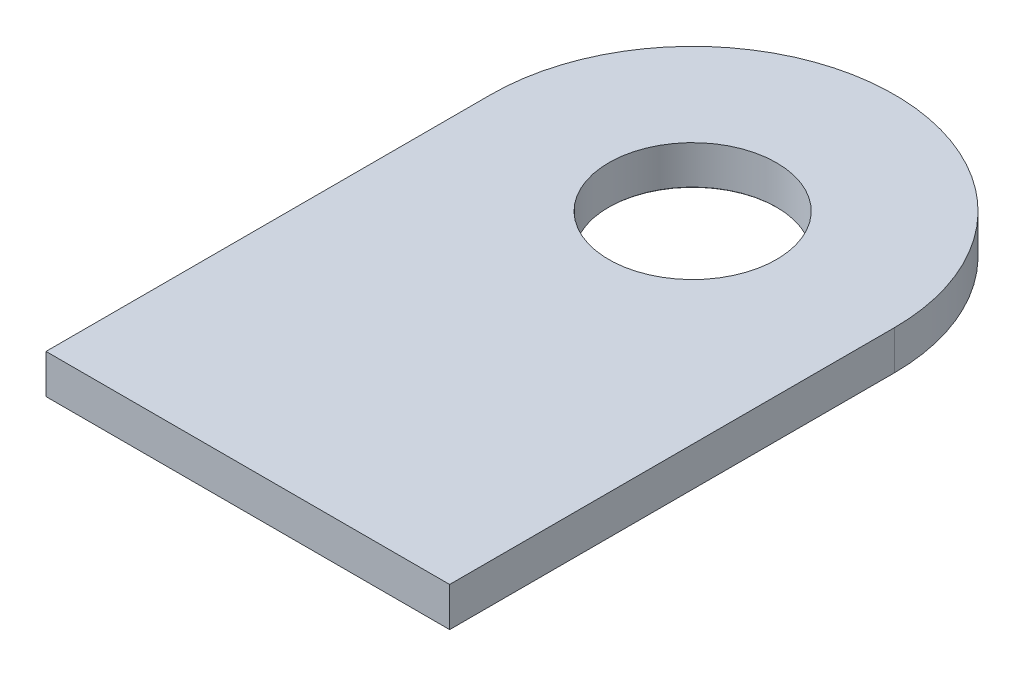
SolidWorks part; units mm, degrees
ref_plane "Front Plane" through (0, 0, 0) normal (0, 0, 1) x (1, 0, 0)
ref_plane "Top Plane" through (0, 0, 0) normal (0, 1, 0) x (1, 0, 0)
ref_plane "Right Plane" through (0, 0, 0) normal (1, 0, 0) x (0, 0, -1)
sketch "Sketch1" plane through (0, 0, 0) normal (0, 1, 0) x (1, 0, 0)
  line L0 (-7.94, 0) -> (-7.94, -17.5)
  line L1 (-7.94, -17.5) -> (7.94, -17.5)
  line L2 (7.94, -17.5) -> (7.94, 0)
  circle A0 centre (0, 0) radius 7.94
  dimension "D1" = 15.88
  dimension "D2" = 17.5
extrude "Boss-Extrude1" add sketch "Sketch1" along normal blind 1.54 contours A0 | A0 L0 L1 L2
hole_wizard "M6 Clearance Hole1" positions "Sketch4" profile "Sketch3" hole size "M6" standard "ANSI Metric" end condition through all
sketch "Sketch4" plane through (0, 0, 0) normal (0, -1, 0) x (-1, 0, 0)
  point P0 (0, 0)
sketch "Sketch3" plane through (0, 0, 0) normal (1, 0, 0) x (0, 0, -1)
  line L0 (0, 0) -> (0, 1.54)
  line L1 (0, 1.54) -> (3.3, 1.54)
  line L2 (3.3, 1.54) -> (3.3, 0.025)
  line L3 (3.3, 0.025) -> (3.325, 0)
  line L5 (3.325, 0) -> (0, 0)
  line L6 (-3.3, 0.025) -> (-3.325, 0) construction
  line L11 (0, -6.35) -> (0, 107.95) construction
  dimension "Thru Hole Dia." = 6.6
  dimension "Thru Hole Depth" = 1.54
  dimension "Near C'Sink Dia." = 6.65
  dimension "Near C'Sink Angle" = 90
